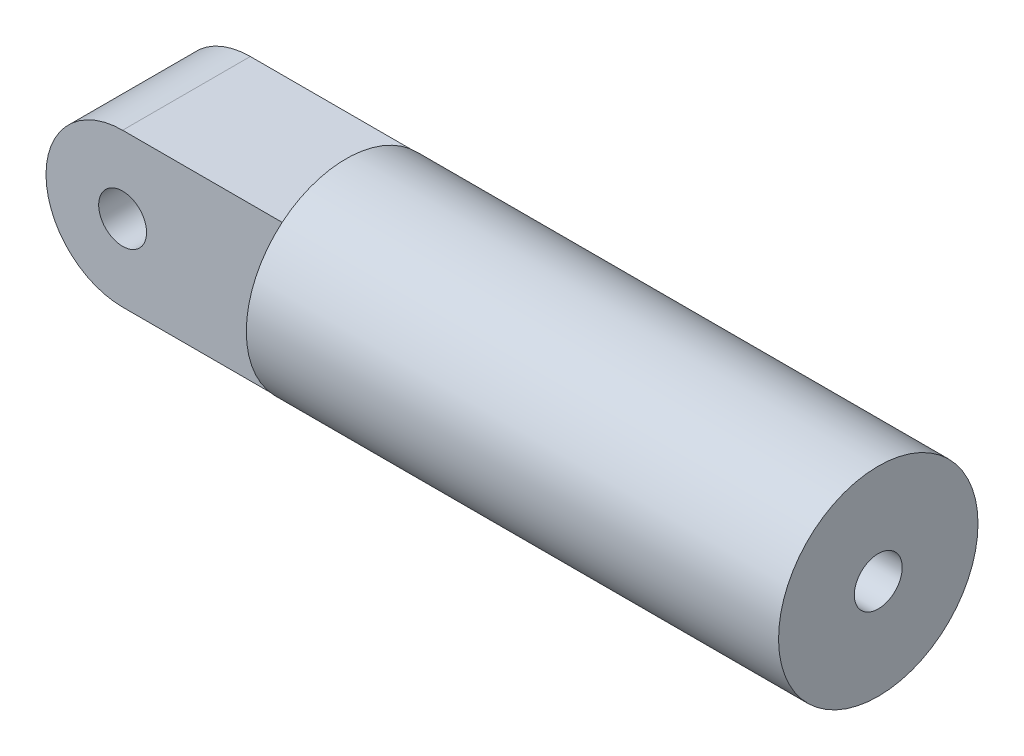
SolidWorks part; units mm, degrees
ref_plane "Front Plane" through (0, 0, 0) normal (0, 0, 1) x (1, 0, 0)
ref_plane "Top Plane" through (0, 0, 0) normal (0, 1, 0) x (1, 0, 0)
ref_plane "Right Plane" through (0, 0, 0) normal (1, 0, 0) x (0, 0, -1)
sketch "Sketch1" plane through (0, 0, 0) normal (1, 0, 0) x (0, 0, -1)
  circle A0 centre (0, 0) radius 12.5
  dimension "D1" = 25
extrude "Boss-Extrude1" add sketch "Sketch1" along normal blind 66.71
sketch "Sketch2" plane through (0, 0, 0) normal (-1, 0, 0) x (0, 0, 1)
  line L1 (-8.0035, -9.6018) -> (8.0035, -9.6018)
  line L2 (-8.0035, -9.6018) -> (-8.0035, 9.6018)
  line L3 (-8.0035, 9.6018) -> (8.0035, 9.6018)
  line L4 (8.0035, -9.6018) -> (8.0035, 9.6018)
  line L5 (-8.0035, -9.6018) -> (8.0035, 9.6018) construction
  line L6 (-8.0035, 9.6018) -> (8.0035, -9.6018) construction
  circle A0 centre (0, 0) radius 12.5 construction
  point P0 (0, 0)
  dimension "D1" = 16.007
extrude "Boss-Extrude2" add sketch "Sketch2" along normal blind 20
sketch "Sketch3" plane through (0, 0, 8.0035) normal (0, 0, 1) x (1, 0, 0)
  line L0 (-20, -9.6018) -> (-20, 9.6018) construction
  line L1 (-20, 9.6018) -> (-20, -9.6018)
  arc A0 (-20, 9.6018) -> (-20, -9.6018) centre (-20, 0) ccw
extrude "Boss-Extrude3" add sketch "Sketch3" against normal up to vertex (16.007 mm away)
sketch "Sketch4" plane through (0, 0, 8.0035) normal (0, 0, 1) x (1, 0, 0)
  line L0 (-20, 9.6018) -> (-20, -9.6018) construction
  circle A0 centre (-20, 0) radius 3
  dimension "D1" = 6
extrude "Cut-Extrude1" cut sketch "Sketch4" against normal through all
sketch "Sketch5" plane through (66.71, 0, 0) normal (1, 0, 0) x (0, 0, -1)
  circle A0 centre (0, 0) radius 3
  dimension "D1" = 6
extrude "Cut-Extrude2" cut sketch "Sketch5" against normal blind 15
cosmetic thread "Cosmetic Thread1" parameters "D2"=10
